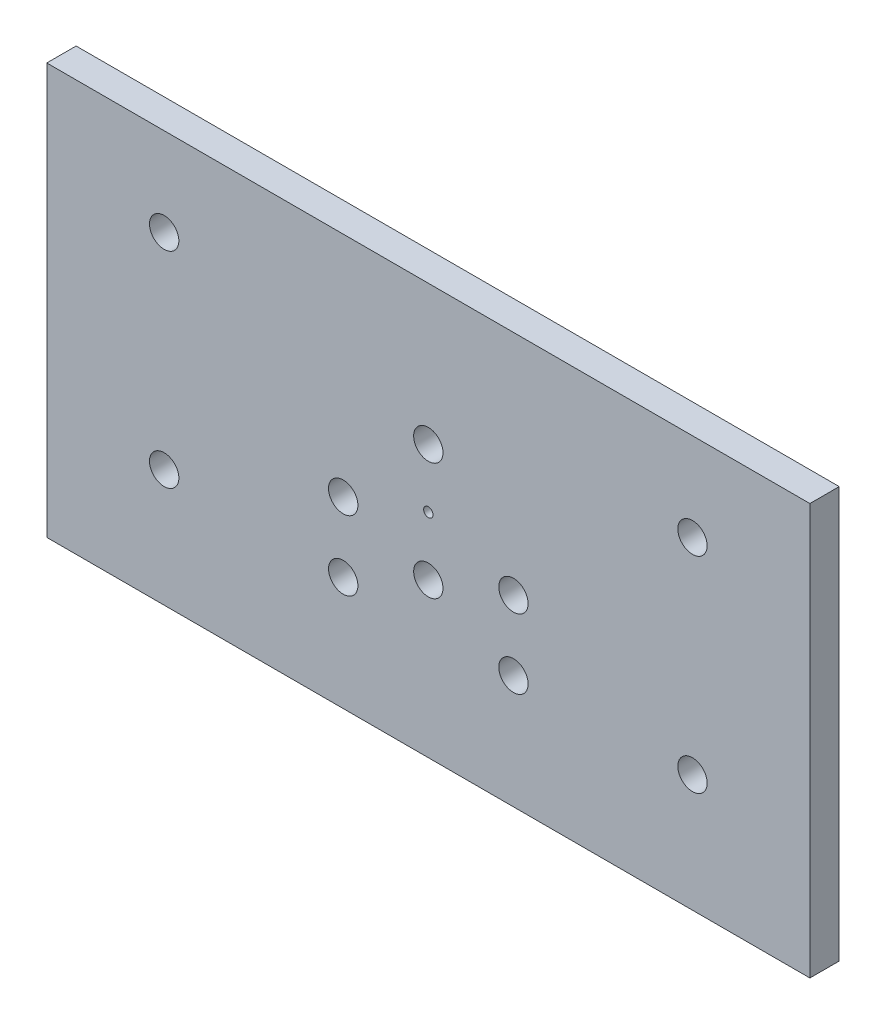
SolidWorks part; units mm, degrees
ref_plane "Plan de face" through (0, 0, 0) normal (0, 0, 1) x (1, 0, 0)
ref_plane "Plan de dessus" through (0, 0, 0) normal (0, 1, 0) x (1, 0, 0)
ref_plane "Plan de droite" through (0, 0, 0) normal (1, 0, 0) x (0, 0, -1)
sketch "Esquisse1" plane through (0, 0, 0) normal (0, 0, 1) x (1, 0, 0)
  line L1 (0, 0) -> (130, 0)
  line L2 (0, 0) -> (0, 70)
  line L3 (0, 70) -> (130, 70)
  line L4 (130, 0) -> (130, 70)
  circle A0 centre (20, 55) radius 2.5
  circle A1 centre (110, 55) radius 2.5
  circle A2 centre (50.5, 31.23) radius 2.5
  circle A3 centre (79.5, 31.23) radius 2.5
  circle A4 centre (50.5, 19.37) radius 2.5
  circle A5 centre (79.5, 19.37) radius 2.5
  circle A6 centre (20, 20) radius 2.5
  circle A7 centre (110, 20) radius 2.5
  dimension "D2" = 15
  dimension "D4" = 5
  dimension "D5" = 15
  dimension "D7" = 5
  dimension "D8" = 5
  dimension "D9" = 5
  dimension "D14" = 19.37
  dimension "D18" = 5
  dimension "D19" = 5
  dimension "D20" = 35
  dimension "D21" = 5
  dimension "D23" = 5
  dimension "D1" = 70
  dimension "130" = 130
  dimension "D3" = 20
  dimension "D6" = 20
  dimension "D10" = 50.5
  dimension "D11" = 50.5
  dimension "D12" = 31.23
  dimension "D13" = 31.23
  dimension "D15" = 19.37
  dimension "D16" = 50.5
  dimension "D17" = 50.5
  dimension "D22" = 20
  dimension "D24" = 35
  dimension "D25" = 20
extrude "Boss.-Extru.4" add sketch "Esquisse1" along normal blind 5
sketch "Esquisse2" plane through (0, 0, 5) normal (0, 0, 1) x (1, 0, 0)
  circle A2 centre (65, 36.23) radius 0.8
  circle A3 centre (65, 26.23) radius 2.5
  circle A4 centre (65, 46.23) radius 2.5
  point P4 (0, 0)
  dimension "D1" = 1.6
  dimension "D2" = 5
  dimension "D3" = 5
  dimension "D4" = 65
  dimension "D5" = 36.23
  dimension "D6" = 10
  dimension "D7" = 10
  dimension "D8" = 65
  dimension "D9" = 65
extrude "Enlèv. mat.-Extru.1" cut sketch "Esquisse2" against normal blind 10
